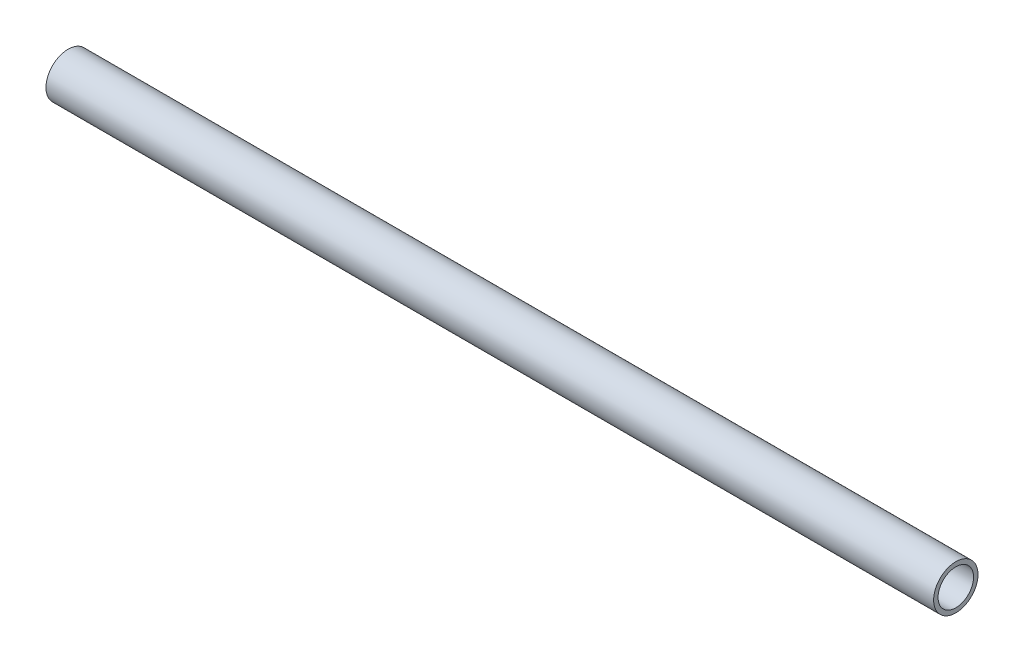
SolidWorks part; units mm, degrees
ref_plane "前视基准面" through (0, 0, 0) normal (0, 0, 1) x (1, 0, 0)
ref_plane "上视基准面" through (0, 0, 0) normal (0, 1, 0) x (1, 0, 0)
ref_plane "右视基准面" through (0, 0, 0) normal (1, 0, 0) x (0, 0, -1)
sketch "草图1" plane through (0, 0, 0) normal (1, 0, 0) x (0, 0, -1)
  circle A0 centre (0, 0) radius 5
  circle A1 centre (0, 0) radius 4
  dimension "D1" = 10
  dimension "D2" = 8
extrude "凸台-拉伸1" add sketch "草图1" along normal mid plane 200
